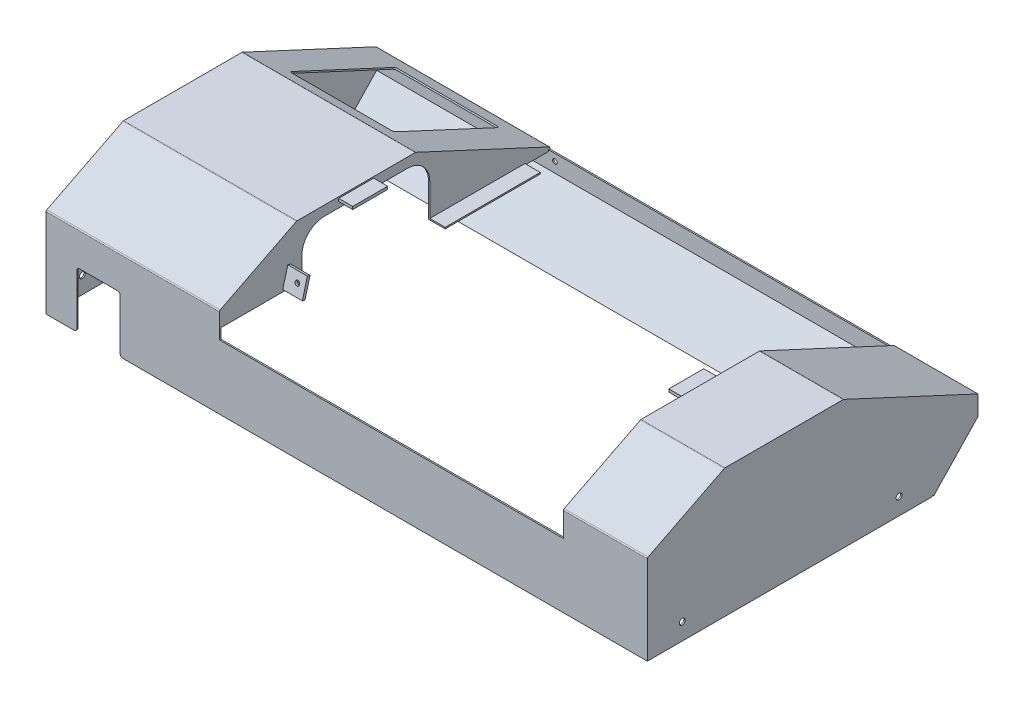
SolidWorks part; units mm, degrees
material "1023 Листовая углеродистая сталь (SS)"
ref_plane "Спереди" through (0, 0, 0) normal (0, 0, 1) x (1, 0, 0)
ref_plane "Сверху" through (0, 0, 0) normal (0, 1, 0) x (1, 0, 0)
ref_plane "Справа" through (0, 0, 0) normal (1, 0, 0) x (0, 0, -1)
sketch "Эскиз1" plane through (0, 0, 0) normal (1, 0, 0) x (0, 0, -1)
  line L0 (-97.8173, 64) -> (-97.8173, 0)
  line L1 (138.6226, 47.3185) -> (138.6226, 33.3185)
  line L2 (-42.5, 92) -> (42.5, 92)
  line L3 (-97.8173, 64) -> (-42.5, 92)
  line L4 (42.5, 92) -> (138.6226, 47.3185)
  line L5 (138.6226, 33.3185) -> (106.907, 0)
  line L6 (137.6226, 33.7183) -> (106.1827, 0.6895)
  line L7 (137.6226, 46.6806) -> (137.6226, 33.7183)
  line L8 (42.2789, 91) -> (137.6226, 46.6806)
  line L9 (-42.2613, 91) -> (42.2789, 91)
  line L10 (-96.8173, 63.3854) -> (-42.2613, 91)
  line L11 (-96.8173, 63.3854) -> (-96.8173, 0)
  line L12 (-96.8173, 0) -> (-97.8173, 0)
  line L13 (106.907, 0) -> (106.1827, 0.6895)
  point P8 (0, 92)
  dimension "D1" = 14
  dimension "D2" = 64
  dimension "D3" = 85
  dimension "D4" = 203
  dimension "D5" = 92
  dimension "D6" = 62
  dimension "D7" = 106
  dimension "D8" = 46
  dimension "D9" = 1
extrude "Бобышка-Вытянуть1" add sketch "Эскиз1" along normal mid plane 430
sketch "Эскиз2" plane through (215, 0, 0) normal (1, 0, 0) x (0, 0, -1)
  line L0 (-96.8173, 0) -> (-96.8173, 63.3854)
  line L1 (-96.8173, 63.3854) -> (-42.2613, 91)
  line L2 (-42.2613, 91) -> (42.2789, 91)
  line L3 (42.2789, 91) -> (137.6226, 46.6806)
  line L4 (137.6226, 46.6806) -> (137.6226, 33.7183)
  line L5 (137.6226, 33.7183) -> (105.5264, 0)
  line L6 (137.6226, 33.7183) -> (106.1827, 0.6895) construction
  line L7 (-96.8173, 0) -> (105.5264, 0)
extrude "Бобышка-Вытянуть2" add sketch "Эскиз2" against normal blind 1
sketch "Эскиз3" plane through (-215, 0, 0) normal (-1, 0, 0) x (0, 0, 1)
  line L0 (96.8173, 0) -> (96.8173, 63.3854)
  line L1 (96.8173, 63.3854) -> (42.2613, 91)
  line L2 (42.2613, 91) -> (-42.2789, 91)
  line L3 (-42.2789, 91) -> (-137.6226, 46.6806)
  line L4 (-137.6226, 46.6806) -> (-137.6226, 33.7183)
  line L5 (-137.6226, 33.7183) -> (-105.5264, 0)
  line L6 (-105.5264, 0) -> (96.8173, 0)
extrude "Бобышка-Вытянуть3" add sketch "Эскиз3" against normal blind 1
sketch "Эскиз4" plane through (0, 0, 97.8173) normal (0, 0, 1) x (1, 0, 0)
  line L0 (-215, 64) -> (-215, 0) construction
  line L1 (-91, 183.9916) -> (155, 183.9916)
  line L2 (-91, 183.9916) -> (-91, 46)
  line L3 (-91, 46) -> (155, 46)
  line L4 (155, 183.9916) -> (155, 46)
  line L5 (215, 0) -> (-215, 0) construction
  dimension "D1" = 60
  dimension "D2" = 124
  dimension "D3" = 46
extrude "Вырез-Вытянуть1" cut sketch "Эскиз4" against normal through all
sketch "Эскиз5" plane through (0, 91.8986, -42.718) normal (0, 0.9068, -0.4215) x (1, 0, 0)
  line L0 (-215, 105.7596) -> (-215, -0.2404) construction
  line L1 (-115.7, 93.3596) -> (-190.3, 93.3596)
  line L2 (-115.7, 93.3596) -> (-115.7, 9.7596)
  line L3 (-115.7, 9.7596) -> (-190.3, 9.7596)
  line L4 (-190.3, 93.3596) -> (-190.3, 9.7596)
  line L5 (-91, -0.2404) -> (-215, -0.2404) construction
  dimension "D1" = 74.6
  dimension "D2" = 83.6
  dimension "D3" = 24.7
  dimension "D4" = 10
extrude "Вырез-Вытянуть2" cut sketch "Эскиз5" against normal up to next contours L3 L4 L1 L2
fillet "Скругление1" radius 2 4 edges at (-115.7, 52.092, -127.1673) (-190.3, 52.092, -127.1673) (-115.7, 87.3314, -51.3574) (-190.3, 87.3314, -51.3574)
sketch "Эскиз7" plane through (0, 0, 97.8173) normal (0, 0, 1) x (1, 0, 0)
  line L0 (215, 0) -> (-215, 0) construction
  line L1 (-193, 0) -> (-162, 0)
  line L2 (-193, 0) -> (-193, 40)
  line L3 (-193, 40) -> (-162, 40)
  line L4 (-162, 0) -> (-162, 40)
  line L5 (-215, 64) -> (-215, 0) construction
  dimension "D1" = 31
  dimension "D2" = 40
  dimension "D3" = 22
extrude "Вырез-Вытянуть3" cut sketch "Эскиз7" against normal up to next
fillet "Скругление2" radius 2 4 edges at (-162, 40, 97.3173) (-193, 40, 97.3173) (-193, 0, 97.3173) (-162, 0, 97.3173)
fillet "Скругление3" radius 1 15 edges at (185, 64, 97.8173) (185, 92, 42.5) (185, 92, -42.5) (0, 33.3185, -138.6226) (-153, 47.3185, -138.6226) (-153, 92, -42.5) (-153, 92, 42.5) (-153, 64, 97.8173) (-152.5, 91, -42.2789) (-152.5, 91, 42.2613) (-152.5, 63.3854, 96.8173) (184.5, 46.6806, -137.6226) (184.5, 91, -42.2789) (184.5, 91, 42.2613) (184.5, 63.3854, 96.8173)
sketch "Эскиз10" plane through (-215, 0, 0) normal (-1, 0, 0) x (0, 0, 1)
  point P0 (-82.1827, 12)
  point P1 (72.8173, 12)
hole_wizard "Сверло под метчик  спиральное M41" positions "Эскиз11" profile "Эскиз12" hole size "M4x0.7" standard "DIN" end condition through all
sketch "Эскиз11" plane through (-215, 0, 0) normal (-1, 0, 0) x (0, 0, 1)
  point P0 (72.8173, 12)
  point P3 (-82.1827, 12)
sketch "Эскиз12" plane through (-215, 12, 72.8173) normal (0, 1, 0) x (0, 0, 1)
  line L0 (0, 0) -> (0, 430)
  line L1 (0, 430) -> (2.1, 430)
  line L2 (2.1, 430) -> (2.1, 0)
  line L5 (2.1, 0) -> (0, 0)
  line L11 (0, -6.35) -> (0, 107.95) construction
  dimension "Диаметр сквозного отверстия" = 4.2
  dimension "Глубина сквозного отверстия" = 430
ref_plane "Плоскость1" through (32, 0, 0) normal (1, 0, 0) x (0, 0, -1)
sketch "Эскиз13" plane through (-91, 0, 0) normal (1, 0, 0) x (0, 0, -1)
  line L0 (137.6226, 45) -> (137.6226, 46.6806)
  line L1 (137.6226, 46.6806) -> (42.2789, 91)
  line L2 (42.2789, 91) -> (-42.2613, 91)
  line L3 (-42.2613, 91) -> (-96.8173, 63.3854)
  line L4 (-96.8173, 63.3854) -> (-96.8173, 53)
  line L5 (-96.8173, 62.7707) -> (-96.8173, 46) construction
  line L6 (-96.8173, 53) -> (-38.8173, 53)
  line L7 (-38.8173, 53) -> (-38.8173, 69)
  line L8 (-22.8173, 85) -> (36.6226, 85)
  line L9 (52.6226, 69) -> (52.6226, 45)
  line L10 (52.6226, 45) -> (137.6226, 45)
  line L12 (137.6226, 46.6806) -> (42.4794, 90.9068) construction
  line L13 (42.0579, 91) -> (-42.0227, 91) construction
  line L14 (-42.4743, 90.8922) -> (-96.2689, 63.6629) construction
  line L15 (137.6226, 46) -> (137.6226, 46.6806) construction
  line L16 (138.6226, 46) -> (137.6226, 46) construction
  line L17 (-97.8173, 63.3854) -> (-97.8173, 46) construction
  line L18 (138.6226, 46.6806) -> (138.6226, 46) construction
  line L19 (-42.2613, 92) -> (42.2789, 92) construction
  arc A2 (-38.8173, 69) -> (-22.8173, 85) centre (-22.8173, 69) cw
  arc A3 (36.6226, 85) -> (52.6226, 69) centre (36.6226, 69) cw
  point P8 (137.4824, 46.7458)
  point P17 (42.2737, 90.9764)
  point P18 (42.2683, 90.9085)
  point P23 (42.2737, 90.9727)
  dimension "D5" = 16
  dimension "D1" = 1
  dimension "D2" = 6
  dimension "D3" = 59
  dimension "D4" = 86
  dimension "D6" = 39
extrude "Бобышка-Вытянуть4" add sketch "Эскиз13" against normal blind 1
sketch "Эскиз14" plane through (-91, 0, 0) normal (1, 0, 0) x (0, 0, -1)
  line L1 (52.6226, 45) -> (120.6226, 45)
  line L2 (52.6226, 45) -> (52.6226, 46)
  line L3 (52.6226, 46) -> (120.6226, 46)
  line L4 (120.6226, 45) -> (120.6226, 46)
  dimension "D1" = 1
  dimension "D2" = 68
extrude "Бобышка-Вытянуть5" add sketch "Эскиз14" along normal blind 11
sketch "Эскиз15" plane through (-91, 0, 0) normal (1, 0, 0) x (0, 0, -1)
  line L0 (-42.2613, 92) -> (42.2789, 92) construction
  line L1 (-12.4912, 91) -> (12.5088, 91)
  line L2 (-12.4912, 91) -> (-12.4912, 89)
  line L3 (-12.4912, 89) -> (12.5088, 89)
  line L4 (12.5088, 91) -> (12.5088, 89)
  point P6 (0.0088, 91)
  point P7 (0.0088, 92)
  dimension "D1" = 2
  dimension "D2" = 1
  dimension "D3" = 25
extrude "Бобышка-Вытянуть6" add sketch "Эскиз15" along normal blind 10
sketch "Эскиз16" plane through (-91, 0, 0) normal (1, 0, 0) x (0, 0, -1)
  line L0 (-52.5295, 54.5176) -> (-48.9061, 68.0406)
  line L1 (-48.9061, 68.0406) -> (-46.9742, 67.523)
  line L2 (-46.9742, 67.523) -> (-50.5977, 54)
  line L3 (-50.5977, 54) -> (-52.5295, 54.5176)
  line L4 (-42.4935, 91.9727) -> (-45.3402, 81.3486) construction
  line L5 (-38.8173, 53) -> (-38.8173, 69) construction
  arc A0 (-42.2613, 92) -> (-42.7129, 91.8922) centre (-42.2613, 91) ccw construction
  point P9 (0, 0)
  dimension "D1" = 2
  dimension "D2" = 14
  dimension "D3" = 1
  dimension "D4" = 165
extrude "Бобышка-Вытянуть7" add sketch "Эскиз16" along normal blind 14
mirror "Зеркальное отражение1" about plane through (32, 0, 0) normal (1, 0, 0) of "Бобышка-Вытянуть4", "Бобышка-Вытянуть5", "Бобышка-Вытянуть6", "Бобышка-Вытянуть7"
hole_wizard "Отверстие обработанное метчиком M41" positions "Эскиз17" profile "Эскиз19" tap size "M4" standard "DIN"
sketch "Эскиз17" plane through (0, 0, -138.6226) normal (0, 0, -1) x (-1, 0, 0)
  point P0 (-150.5, 41)
  point P3 (86.5, 41)
sketch "Эскиз19" plane through (150.5, 41, -138.6226) normal (1, 0, 0) x (0, 1, 0)
  line L0 (0, 0) -> (0, 1)
  line L1 (0, 1) -> (1.65, 1)
  line L2 (1.65, 1) -> (1.65, 0)
  line L5 (1.65, 0) -> (0, 0)
  line L11 (0, -6.35) -> (0, 107.95) construction
  dimension "Диаметр проходного сверла" = 3.3
  dimension "Глубина проходного сверла" = 1
cosmetic thread "Отверстие резьбы1" parameters "D2"=4
cosmetic thread "Отверстие резьбы2" parameters "D2"=4
hole_wizard "Отверстие обработанное метчиком M42" positions "Эскиз20" profile "Эскиз21" tap size "M4" standard "DIN"
sketch "Эскиз20" plane through (0, 16.7844, 62.6401) normal (0, 0.2588, 0.9659) x (1, 0, 0)
  point P0 (-82.5, 46.5637)
  point P3 (146.5, 46.5637)
sketch "Эскиз21" plane through (-82.5, 61.7615, 50.5885) normal (1, 0, 0) x (0, -0.9659, 0.2588)
  line L0 (0, 0) -> (0, 2)
  line L1 (0, 2) -> (1.65, 2)
  line L2 (1.65, 2) -> (1.65, 0)
  line L5 (1.65, 0) -> (0, 0)
  line L11 (0, -6.35) -> (0, 107.95) construction
  dimension "Диаметр проходного сверла" = 3.3
  dimension "Глубина проходного сверла" = 2
cosmetic thread "Отверстие резьбы3" parameters "D2"=4
cosmetic thread "Отверстие резьбы4" parameters "D2"=4
